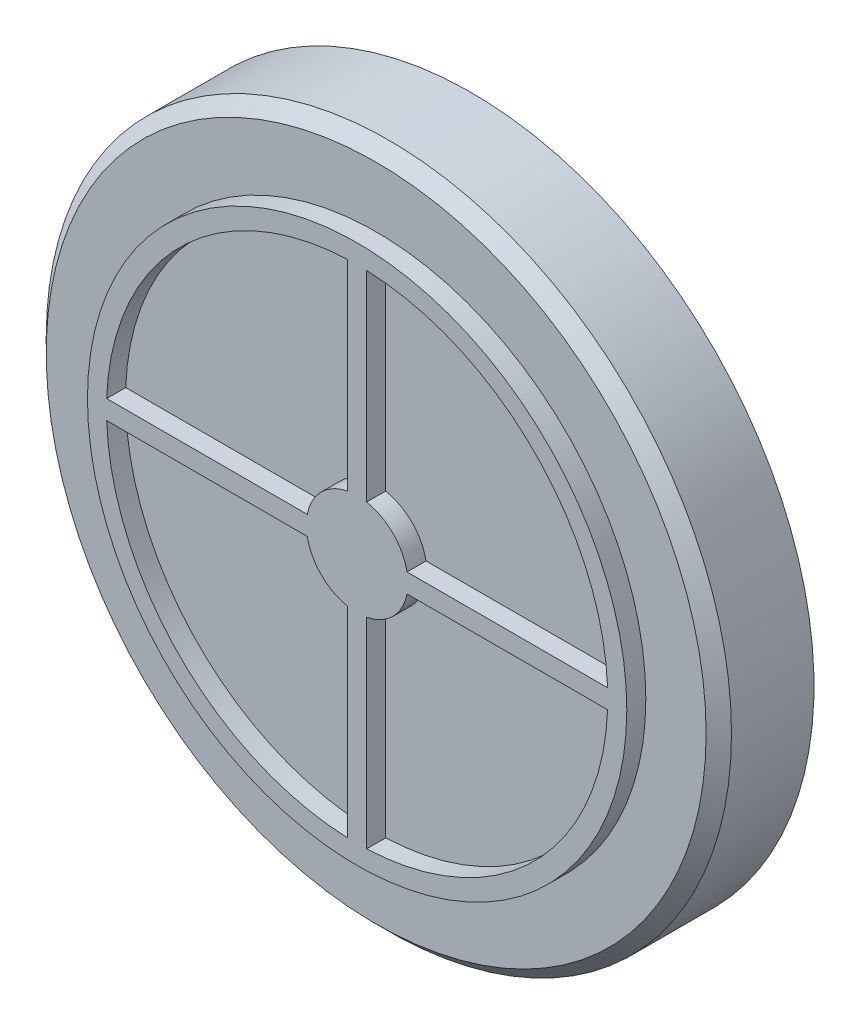
SolidWorks part; units mm, degrees
ref_plane "Спереди" through (0, 0, 0) normal (0, 0, 1) x (1, 0, 0)
ref_plane "Сверху" through (0, 0, 0) normal (0, 1, 0) x (1, 0, 0)
ref_plane "Справа" through (0, 0, 0) normal (1, 0, 0) x (0, 0, -1)
other "Configuration Table"
sketch "Эскиз1" plane through (0, 0, 0) normal (0, 1, 0) x (1, 0, 0)
  line L6 (0, 0) -> (-54, 0)
  line L7 (-54, 0) -> (-54, 145)
  line L8 (-54, 145) -> (-51, 145)
  line L9 (-51, 145) -> (-51, 3)
  line L10 (-51, 3) -> (0, 3)
  line L11 (0, 3) -> (0, 0)
  dimension "D1" = 3
  dimension "D2" = 3
  dimension "D3" = 145
  dimension "D4" = 54
revolve "Повернуть1" add sketch "Эскиз1" angle 360 about L11
ref_plane "Плоскость2" through (57, 0, 0) normal (1, 0, 0) x (0, 0, -1)
sketch "Эскиз2" plane through (57, 0, 0) normal (1, 0, 0) x (0, 0, -1)
  line L0 (145, 14) -> (145, -14)
  line L1 (145, -54) -> (145, 54) construction
  line L2 (145, -14) -> (140, -14)
  line L3 (140, -14) -> (138.5, 11)
  line L4 (138.5, 11) -> (134, 11)
  line L5 (134, 11) -> (134, 14)
  line L6 (134, 14) -> (145, 14)
  point P8 (0, 0)
  dimension "D1" = 28
  dimension "D2" = 3
  dimension "D3" = 6.5
  dimension "D4" = 11
  dimension "D5" = 5
  dimension "D6" = 14
extrude "Бобышка-Вытянуть1" add sketch "Эскиз2" against normal blind 10
fillet "Скругление1" radius 2 1 edges at (54.5768, -14, -140)
pattern_circular "Круговой массив2" count 3 over 360 about axis through (0, 0, 0) along (0, 0, 1) of "Бобышка-Вытянуть1", "Скругление1"
sketch "Эскиз3" plane through (0, 0, -145) normal (0, 0, -1) x (-1, 0, 0)
  circle A0 centre (0, 0) radius 51
extrude "Вырез-Вытянуть1" cut sketch "Эскиз3" against normal blind 15
sketch "Эскиз4" plane through (0, 0, -145) normal (0, 0, -1) x (-1, 0, 0)
  circle A0 centre (0, 0) radius 57
  circle A1 centre (0, 0) radius 62.6187
extrude "Вырез-Вытянуть2" cut sketch "Эскиз4" against normal blind 15
chamfer "Фаска1" distance 2 angle 45 1 edges at (-54, 0, 0)
sketch "Эскиз5" plane through (0, 0, 0) normal (0, 0, 1) x (1, 0, 0)
  circle A0 centre (0, 0) radius 42.5
  dimension "D1" = 85
fillet "Скругление2" radius 5 1 edges at (-51, 0, -3)
extrude "Бобышка-Вытянуть2" add sketch "Эскиз5" along normal blind 3
sketch "Эскиз7" plane through (0, 0, 3) normal (0, 0, 1) x (1, 0, 0)
  circle A0 centre (0, 0) radius 39.5
  dimension "D1" = 79
extrude "Вырез-Вытянуть3" cut sketch "Эскиз7" against normal up to surface (3 mm away) up to face at (42.5, 0, 0)
sketch "Эскиз8" plane through (0, 0, 0) normal (0, 0, 1) x (1, 0, 0)
  line L0 (-1.5, -41) -> (-1.5, 41)
  line L1 (-1.5, -41) -> (1.5, -41)
  line L2 (-1.5, 41) -> (1.5, 41)
  line L3 (1.5, -41) -> (1.5, 41)
  line L4 (-1.5, -41) -> (1.5, 41) construction
  line L5 (-1.5, 41) -> (1.5, -41) construction
  line L6 (-41, -1.5) -> (41, -1.5)
  line L7 (-41, -1.5) -> (-41, 1.5)
  line L8 (41, -1.5) -> (41, 1.5)
  line L9 (-41, 1.5) -> (41, 1.5)
  line L10 (-41, -1.5) -> (41, 1.5) construction
  line L11 (41, -1.5) -> (-41, 1.5) construction
  circle A0 centre (0, 0) radius 8
  circle M1 centre (0, 0) radius 39.5
  dimension "D1" = 16
  dimension "D2" = 3
  dimension "D3" = 82
  dimension "D4" = 82
  dimension "D5" = 3
extrude "Бобышка-Вытянуть4" add sketch "Эскиз8" along normal blind 3 contours A0 L3 L0 M1 | L3 A0 L0 L9 | L9 A0 L3 | L6 A0 L9 L3 | A0 L6 L9 M1 | L3 A0 L6 | L0 A0 L3 L6 | L9 L0 L6 L3 | L0 A0 L9 | L9 A0 L6 L0 | A0 L9 L6 M1 | L6 A0 L0 | A0 L0 L3 M1
sketch "Эскиз9" plane through (0, 0, -145) normal (0, 0, -1) x (-1, 0, 0)
  circle A0 centre (0, 0) radius 73.1795
extrude "Вырез-Вытянуть4" cut sketch "Эскиз9" against normal blind 130
equation "\"d\"=3"
equation "\"D1@Эскиз1\"=\"d\""
equation "\"D2@Эскиз1\"=\"d\""
